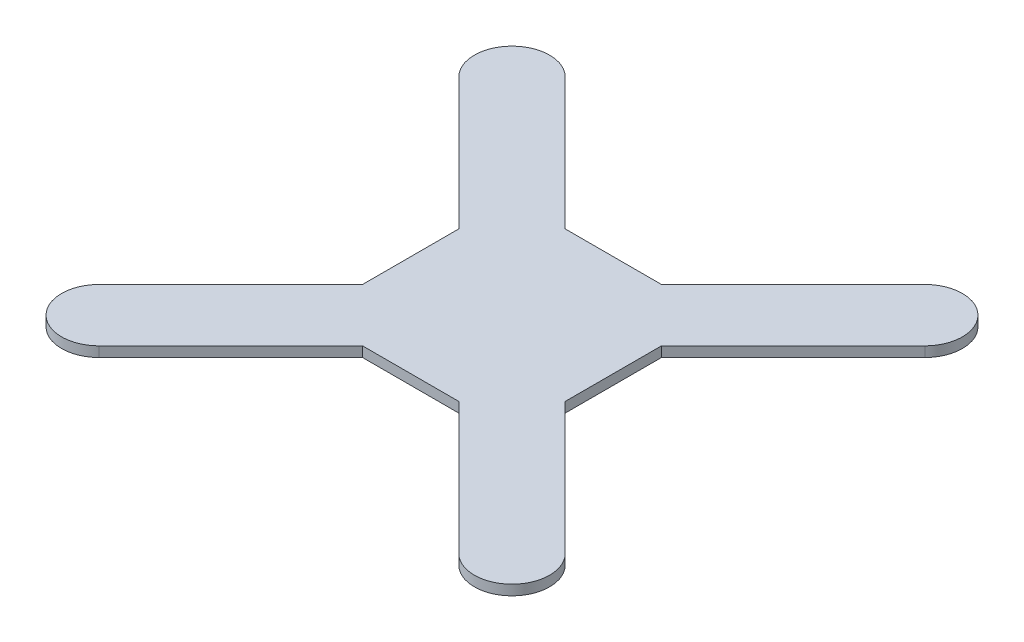
SolidWorks part; units mm, degrees
ref_plane "Front Plane" through (0, 0, 0) normal (0, 0, 1) x (1, 0, 0)
ref_plane "Top Plane" through (0, 0, 0) normal (0, 1, 0) x (1, 0, 0)
ref_plane "Right Plane" through (0, 0, 0) normal (1, 0, 0) x (0, 0, -1)
sketch "Sketch1" plane through (0, 0, 0) normal (0, 1, 0) x (1, 0, 0)
  line L0 (277.5, -130) -> (407.5, 0)
  line L5 (130, -130) -> (330, -130)
  line L6 (130, -130) -> (130, -330)
  line L7 (130, -330) -> (330, -330)
  line L8 (330, -130) -> (330, -330)
  line L9 (330, -182.5) -> (460, -52.5)
  line L10 (230, -130) -> (230, -330) construction
  line L11 (342.5, -65) -> (395, -117.5) construction
  line L12 (130, -182.5) -> (130, -130)
  line L13 (130, -230) -> (330, -230) construction
  line L14 (130, -182.5) -> (0, -52.5)
  line L15 (182.5, -130) -> (52.5, 0)
  line L16 (330, -277.5) -> (460, -407.5)
  line L17 (277.5, -330) -> (407.5, -460)
  line L18 (130, -277.5) -> (0, -407.5)
  line L19 (182.5, -330) -> (52.5, -460)
  line L20 (182.5, -130) -> (130, -130)
  line L21 (277.5, -130) -> (330, -130)
  line L22 (330, -182.5) -> (330, -130)
  line L23 (182.5, -330) -> (130, -330)
  line L24 (130, -277.5) -> (130, -330)
  line L25 (277.5, -330) -> (330, -330)
  line L26 (330, -277.5) -> (330, -330)
  arc A0 (0, -407.5) -> (52.5, -460) centre (26.25, -433.75) ccw
  arc A1 (407.5, -460) -> (460, -407.5) centre (433.75, -433.75) ccw
  arc A2 (460, -52.5) -> (407.5, 0) centre (433.75, -26.25) ccw
  arc A3 (52.5, 0) -> (0, -52.5) centre (26.25, -26.25) ccw
  dimension "D2" = 200
  dimension "D3" = 200
  dimension "D7" = 95
  dimension "D8" = 95
  dimension "D9" = 45
  dimension "D10" = 45
extrude "Boss-Extrude1" add sketch "Sketch1" along normal blind 10 contours L8 L5 L6 L7 | L18 A0 L19 L7 L6 | L15 A3 L14 L6 L5 | L9 A2 L0 L5 L8 | L17 A1 L16 L8 L7
